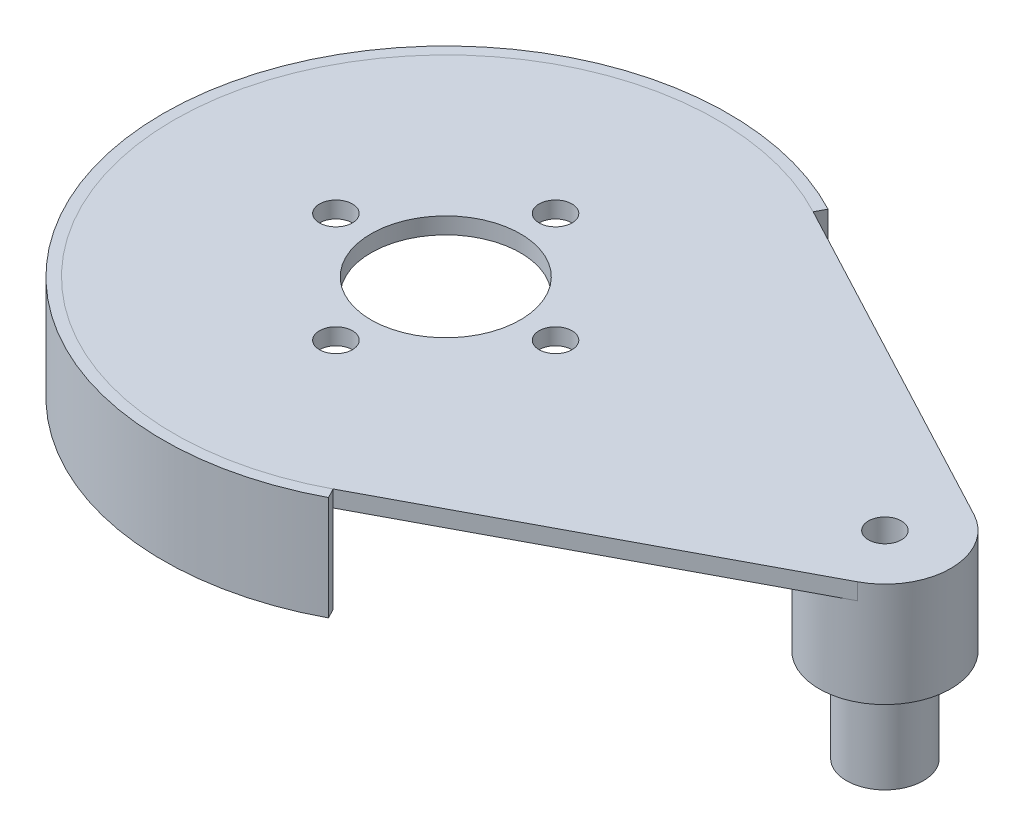
SolidWorks part; units mm, degrees
ref_plane "前视基准面" through (0, 0, 0) normal (0, 0, 1) x (1, 0, 0)
ref_plane "上视基准面" through (0, 0, 0) normal (0, 1, 0) x (1, 0, 0)
ref_plane "右视基准面" through (0, 0, 0) normal (1, 0, 0) x (0, 0, -1)
other "Configuration Table"
sketch "草图2" plane through (0, 0, 0) normal (0, 1, 0) x (1, 0, 0)
  line L0 (0, 0) -> (40, 0)
  line L1 (11.6016, 21.8624) -> (42.8125, 5.3)
  line L2 (11.6016, -21.8624) -> (42.8125, -5.3)
  circle A0 centre (0, 0) radius 24.75
  circle A2 centre (40, 0) radius 6
  circle A3 centre (51.2114, 1.2599) radius 0.153
  dimension "D1" = 49.5
  dimension "D2" = 40
  dimension "D3" = 12
extrude "凸台-拉伸1" add sketch "草图2" along normal blind 1.5
sketch "草图3" plane through (0, 0, 0) normal (0, -1, 0) x (1, 0, 0)
  line L0 (0, 0) -> (11.6016, 21.8624)
  line L1 (0, 0) -> (11.6016, -21.8624)
  line L2 (11.6016, 21.8624) -> (12.0703, 22.7458)
  line L3 (11.6016, -21.8624) -> (12.0703, -22.7458)
  circle A0 centre (0, 0) radius 24.75
  circle A1 centre (0, 0) radius 25.75
  arc M7 (11.6016, 21.8624) -> (11.6016, -21.8624) centre (0, 0) ccw
  dimension "D1" = 49.5
  dimension "D2" = 51.5
extrude "凸台-拉伸2" add sketch "草图3" along normal blind 8 and the other way blind 1.5 separate body contours L2 A1 L3 M7 | A0
ref_plane "基准面1" through (11.6016, 1.5, -21.8624) normal (0, -1, 0) x (-1, 0, 0)
sketch "草图5" plane through (0, 1.5, 0) normal (0, 1, 0) x (1, 0, 0)
  circle A0 centre (0, 0) radius 6.8
  circle A1 centre (0, 0) radius 10 construction
  circle A2 centre (0, 10) radius 1.5
  circle A3 centre (10, 0) radius 1.5
  circle A4 centre (0, -10) radius 1.5
  circle A5 centre (-10, 0) radius 1.5
  point P6 (0, 0)
  point P15 (0, 0)
  dimension "D1" = 13.6
  dimension "D2" = 20
  dimension "D3" = 3
  dimension "D4" = 4
extrude "切除-拉伸1" cut sketch "草图5" against normal through all
sketch "草图6" plane through (0, 0, 0) normal (0, -1, 0) x (1, 0, 0)
  circle A0 centre (40, 0) radius 6
  dimension "D1" = 12
extrude "凸台-拉伸3" add sketch "草图6" along normal blind 8
sketch "草图7" plane through (0, -8, 0) normal (0, -1, 0) x (1, 0, 0)
  circle A0 centre (40, 0) radius 3.5
  dimension "D1" = 7
extrude "凸台-拉伸4" add sketch "草图7" along normal blind 8.5
sketch "草图9" plane through (0, -16.5, 0) normal (0, -1, 0) x (1, 0, 0)
  circle A0 centre (40, 0) radius 1.5
  dimension "D1" = 3
extrude "切除-拉伸2" cut sketch "草图9" against normal through all
